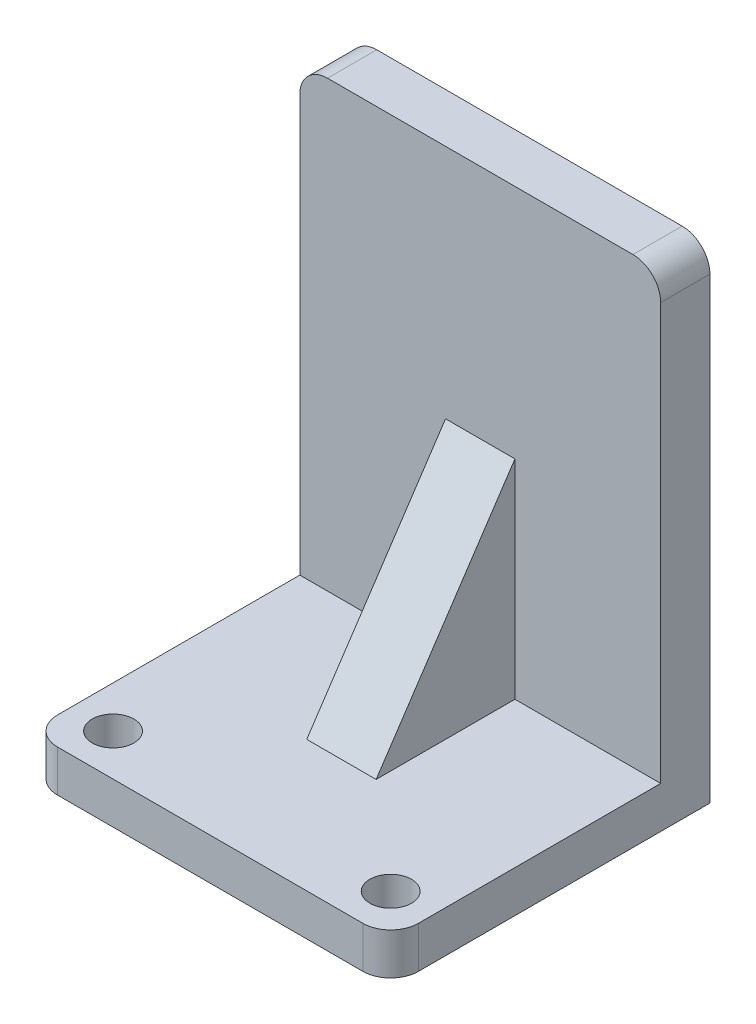
SolidWorks part; units mm, degrees
material "6061 Alloy"
ref_plane "Front Plane" through (0, 0, 0) normal (0, 0, 1) x (1, 0, 0)
ref_plane "Top Plane" through (0, 0, 0) normal (0, 1, 0) x (1, 0, 0)
ref_plane "Right Plane" through (0, 0, 0) normal (1, 0, 0) x (0, 0, -1)
sketch "Sketch1" plane through (0, 0, 0) normal (0, 1, 0) x (1, 0, 0)
  line L0 (0, 0) -> (-46792.0861, 0) construction
  line L1 (0, 0) -> (0, 46792.0861) construction
  line L3 (13, 10.5) -> (-13, 10.5)
  line L4 (13, 10.5) -> (13, -10.5)
  line L5 (11, -12.5) -> (-11, -12.5)
  line L6 (-13, 10.5) -> (-13, -10.5)
  line L7 (0, -12.5) -> (0, 10.5) construction
  line L8 (13, 0) -> (-13, 0) construction
  arc A0 (13, -10.5) -> (11, -12.5) centre (11, -10.5) cw
  arc A1 (-11, -12.5) -> (-13, -10.5) centre (-11, -10.5) cw
  circle A2 centre (-10, -9.5) radius 1.5
  circle A3 centre (10, -9.5) radius 1.5
  point P5 (0, 0)
  point P11 (13, -12.5)
  point P14 (-13, -12.5)
  dimension "D3" = 2
  dimension "D4" = 3
  dimension "D5" = 3
  dimension "D6" = 3
  dimension "D7" = 3
  dimension "D8" = 3
  dimension "D9" = 3
  dimension "D1" = 26
  dimension "D2" = 23
extrude "Boss-Extrude1" add sketch "Sketch1" along normal blind 3
sketch "Sketch2" plane through (-13, 0, 0) normal (-1, 0, 0) x (0, 0, 1)
  line L0 (-10.5, 3) -> (10.5, 3) construction
  line L2 (-10.5, 3) -> (-10.5, 35)
  line L3 (-10.5, 35) -> (-6.9535, 35)
  line L4 (-6.9535, 3) -> (-6.9535, 35)
  line L5 (-10.5, 3) -> (-6.9535, 3)
  point P5 (-6.9535, 3)
extrude "Boss-Extrude2" add sketch "Sketch2" against normal blind 26
sketch "Sketch3" plane through (-13, 0, 0) normal (-1, 0, 0) x (0, 0, 1)
  line L0 (-6.9535, 18) -> (3.0465, 3)
  line L1 (-6.9535, 3) -> (3.0465, 3)
  line L2 (-6.9535, 3) -> (-6.9535, 18)
  dimension "D1" = 10
  dimension "D2" = 15
extrude "Boss-Extrude3" add sketch "Sketch3" against normal blind 5 from offset 10.5 offset against normal yes
fillet "Fillet1" radius 2 1 edges at (-13, 35, -8.7268)
fillet "Fillet2" radius 2 1 edges at (13, 35, -8.7268)
equation "\"010.5.00mm\"=0"
